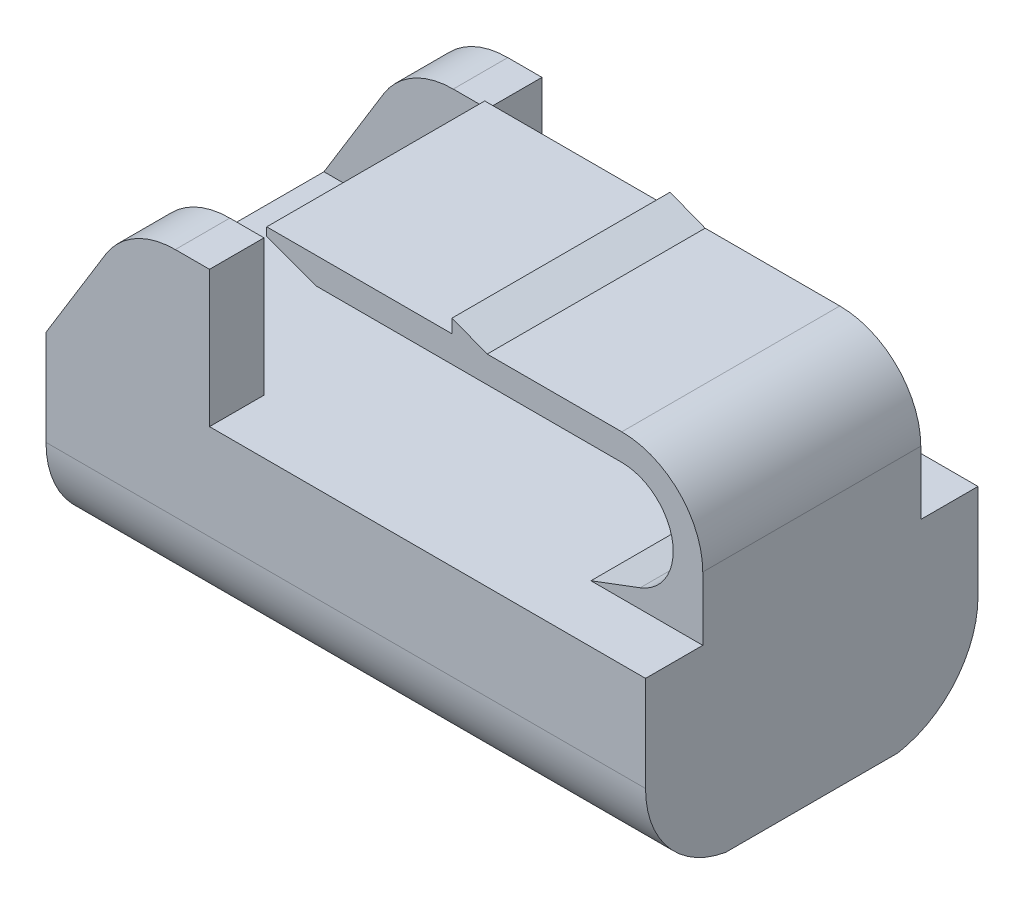
SolidWorks part; units mm, degrees
ref_plane "Front Plane" through (0, 0, 0) normal (0, 0, 1) x (1, 0, 0)
ref_plane "Top Plane" through (0, 0, 0) normal (0, 1, 0) x (1, 0, 0)
ref_plane "Right Plane" through (0, 0, 0) normal (1, 0, 0) x (0, 0, -1)
sketch "Sketch1" plane through (0, 0, 0) normal (0, 1, 0) x (1, 0, 0)
  line L1 (0, 0) -> (22, 0)
  line L2 (0, 0) -> (0, 12.2)
  line L3 (0, 12.2) -> (22, 12.2)
  line L4 (22, 0) -> (22, 12.2)
  dimension "D1" = 22
  dimension "D2" = 12.2
extrude "Boss-Extrude1" add sketch "Sketch1" along normal blind 7
sketch "Sketch2" plane through (22, 0, 0) normal (1, 0, 0) x (0, 0, -1)
  line L0 (0, 3.5) -> (12.2, 3.5) construction
  line L1 (0, 7) -> (0, 0) construction
  line L2 (12.2, 7) -> (12.2, 0) construction
  line L3 (0, 0) -> (12.2, 0) construction
  line L4 (6.1, 7) -> (6.1, 0) construction
  line L5 (0, 7) -> (12.2, 7) construction
  line L6 (0, 3.5) -> (0, 0)
  line L7 (0, 0) -> (2.9413, 0)
  arc A0 (0, 3.5) -> (2.9413, 0) centre (3.5531, 3.5) ccw
extrude "Cut-Extrude2" cut sketch "Sketch2" against normal up to next
sketch "Sketch3" plane through (0, 0, -12.2) normal (0, 0, -1) x (-1, 0, 0)
  line L0 (0, 7) -> (-6, 7)
  line L1 (-22, 7) -> (0, 7) construction
  line L2 (-6, 7) -> (-6, 12)
  line L3 (-6, 12) -> (-4.7446, 12)
  line L4 (-2.1868, 10.5678) -> (0, 7)
  arc A0 (-2.1868, 10.5678) -> (-4.7446, 12) centre (-4.7446, 9) ccw
  dimension "D1" = 3
  dimension "D2" = 5
  dimension "D3" = 6
extrude "Boss-Extrude2" add sketch "Sketch3" against normal blind 2
ref_plane "Plane1" through (0, 0, -6.1) normal (0, 0, 1) x (1, 0, 0)
mirror "Mirror1" about plane through (0, 0, -6.1) normal (0, 0, 1) of "Boss-Extrude2", "Cut-Extrude2"
sketch "Sketch4" plane through (0, 0, -6.1) normal (0, 0, 1) x (1, 0, 0)
  line L0 (17.8957, 7) -> (22, 7)
  line L1 (6, 7) -> (22, 7) construction
  line L2 (22, 7) -> (22, 9.329)
  line L3 (19.029, 12.3) -> (14.0878, 12.3)
  line L4 (6, 12.3) -> (6, 12)
  line L5 (6, 12) -> (7.8157, 11.3272)
  line L6 (7.8157, 11.3272) -> (19.029, 11.3272)
  line L7 (19.7027, 7.6797) -> (17.8957, 7)
  line L8 (14.0878, 12.3) -> (12.8, 12.8)
  line L9 (12.8, 12.8) -> (12.8, 12.3)
  line L10 (22, 7) -> (22, 3.5) construction
  line L11 (0, 0) -> (22, 0) construction
  line L12 (12.8, 12.3) -> (6, 12.3)
  arc A0 (22, 9.329) -> (19.029, 12.3) centre (19.029, 9.329) ccw
  arc A1 (19.029, 11.3272) -> (19.7027, 7.6797) centre (19.029, 9.4413) cw
  dimension "D1" = 9.2
  dimension "D2" = 12.8
  dimension "D3" = 0.5
extrude "Boss-Extrude3" add sketch "Sketch4" along normal blind 4 and the other way blind 4
